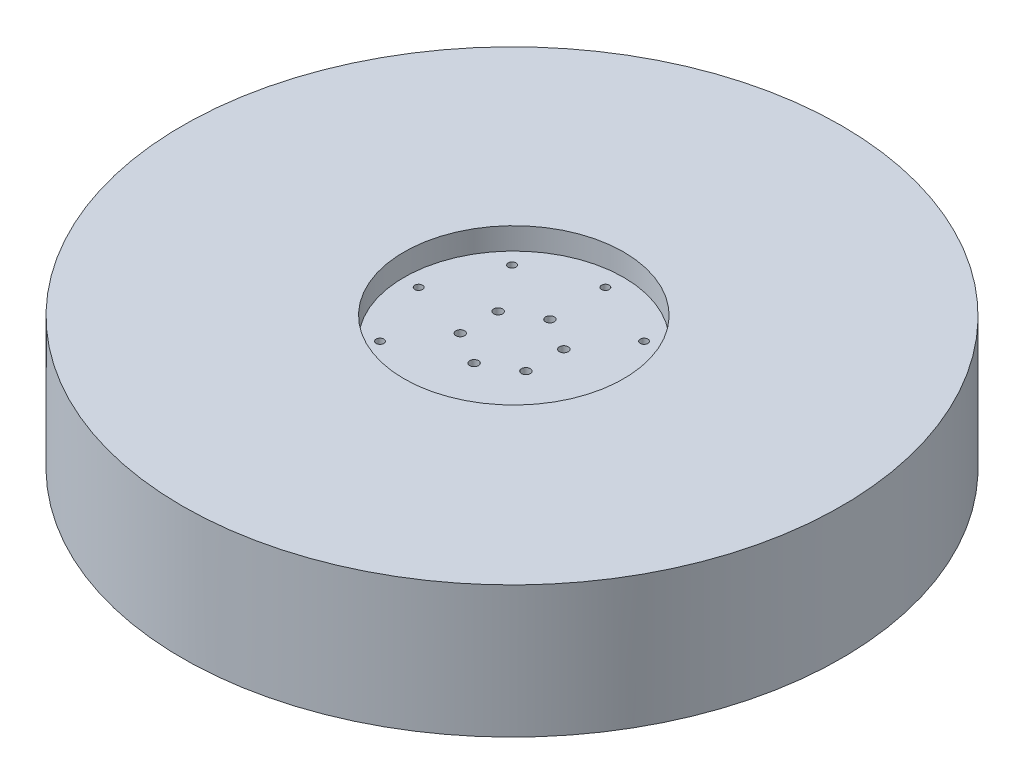
SolidWorks part; units mm, degrees
ref_plane "前视基准面" through (0, 0, 0) normal (0, 0, 1) x (1, 0, 0)
ref_plane "上视基准面" through (0, 0, 0) normal (0, 1, 0) x (1, 0, 0)
ref_plane "右视基准面" through (0, 0, 0) normal (1, 0, 0) x (0, 0, -1)
sketch "草图1" plane through (0, 0, 0) normal (0, 1, 0) x (1, 0, 0)
  circle A0 centre (-17.0916, 0.302) radius 150
  circle A2 centre (-17.0916, 0.302) radius 17.25
  circle A3 centre (-17.0916, 0.302) radius 42.5
  circle A4 centre (-17.0916, 17.552) radius 2
  circle A10 centre (-17.0916, 42.802) radius 1.75
  circle A18 centre (12.9604, 30.354) radius 1.75
  circle A19 centre (25.4084, 0.302) radius 1.75
  circle A20 centre (12.9604, -29.7501) radius 1.75
  circle A21 centre (-17.0916, -42.198) radius 1.75
  circle A22 centre (-47.1437, -29.7501) radius 1.75
  circle A23 centre (-59.5916, 0.302) radius 1.75
  circle A24 centre (-47.1437, 30.354) radius 1.75
  circle A25 centre (-29.2892, 12.4996) radius 2 [skipped]
  circle A26 centre (-29.2892, -11.8956) radius 2 [skipped]
  circle A27 centre (-4.894, -11.8956) radius 2 [skipped]
  circle A28 centre (-4.894, 12.4996) radius 2 [skipped]
  circle A29 centre (-17.0916, -16.948) radius 2 [skipped]
  circle A30 centre (-34.3416, 0.302) radius 2 [skipped]
  circle A31 centre (0.1584, 0.302) radius 2 [skipped]
  circle A32 centre (-2.1527, 8.927) radius 2
  circle A33 centre (-2.1527, -8.323) radius 2
  circle A34 centre (-17.0916, -16.948) radius 2
  circle A35 centre (-32.0306, -8.323) radius 2
  circle A36 centre (-32.0306, 8.927) radius 2
  point P18 (-17.0916, 0.302)
  point P21 (-17.0916, 0.302)
  point P31 (-17.0916, 0.302)
  dimension "D1" = 34.5
  dimension "D2" = 85
  dimension "D3" = 300
  dimension "D4" = 8
  dimension "D5" = 6
extrude "凸台-拉伸2" add sketch "草图1" along normal blind 25
sketch "草图2" plane through (0, 0, 0) normal (0, -1, 0) x (1, 0, 0)
  circle A0 centre (-17.0916, -0.302) radius 29.5
  circle A1 centre (-2.1527, 8.323) radius 2 construction
  dimension "D1" = 59
  dimension "D2" = 17.25
extrude "切除-拉伸1" cut sketch "草图2" against normal blind 6.6
sketch "草图3" plane through (0, 25, 0) normal (0, 1, 0) x (1, 0, 0)
  circle A0 centre (-16.888, 0.9128) radius 50
extrude "切除-拉伸2" cut sketch "草图3" against normal blind 10
sketch "草图10" plane through (0, 0, 0) normal (0, -1, 0) x (1, 0, 0)
  circle A0 centre (-17.0916, -0.302) radius 150
  circle A1 centre (-17.0916, -0.302) radius 150 construction
  circle A2 centre (-17.0916, -0.302) radius 130
  dimension "D1" = 0
extrude "凸台-拉伸7" add sketch "草图10" along normal blind 35
